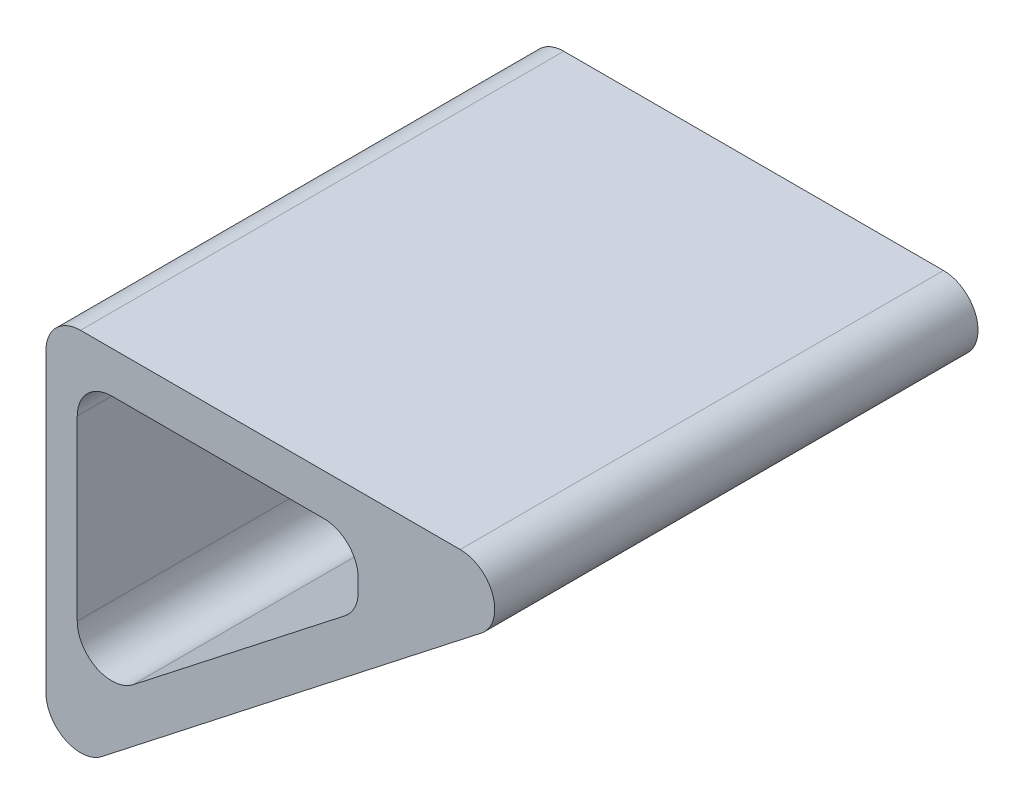
SolidWorks part; units mm, degrees
ref_plane "Front" through (0, 0, 0) normal (0, 0, 1) x (1, 0, 0)
ref_plane "Top" through (0, 0, 0) normal (0, 1, 0) x (1, 0, 0)
ref_plane "Right" through (0, 0, 0) normal (1, 0, 0) x (0, 0, -1)
sketch "Sketch2" plane through (0, 0, 0) normal (0, 0, 1) x (1, 0, 0)
  line L0 (21.0207, 22.9851) -> (-33.9793, 22.9851)
  line L1 (-38.9793, 17.9851) -> (-38.9793, -25.0149)
  line L2 (-30.8997, -28.9539) -> (24.1003, 14.0461)
  line L3 (-34.4531, 11.9981) -> (-34.4531, -13.7378)
  line L4 (-26.3735, -17.6769) -> (4.3255, 6.3241)
  line L5 (6.2459, 10.2632) -> (6.2459, 11.9981)
  line L6 (1.2459, 16.9981) -> (-29.4531, 16.9981)
  arc A0 (-38.9793, -25.0149) -> (-30.8997, -28.9539) centre (-33.9793, -25.0149) ccw
  arc A1 (-34.4531, -13.7378) -> (-26.3735, -17.6769) centre (-29.4531, -13.7378) ccw
  arc A2 (-34.4531, 11.9981) -> (-29.4531, 16.9981) centre (-29.4531, 11.9981) cw
  arc A3 (-33.9793, 22.9851) -> (-38.9793, 17.9851) centre (-33.9793, 17.9851) ccw
  arc A4 (21.0207, 22.9851) -> (24.1003, 14.0461) centre (21.0207, 17.9851) cw
  arc A5 (4.3255, 6.3241) -> (6.2459, 10.2632) centre (1.2459, 10.2632) ccw
  arc A6 (6.2459, 11.9981) -> (1.2459, 16.9981) centre (1.2459, 11.9981) ccw
  dimension "D1" = 5
  dimension "D2" = 5
  dimension "D3" = 48
  dimension "D4" = 55
extrude "Boss-Extrude1" add sketch "Sketch2" along normal blind 70 contours A4 L0 A3 L1 A0 L2 A6 L5 A5 L4 A1 L3 A2 L6
